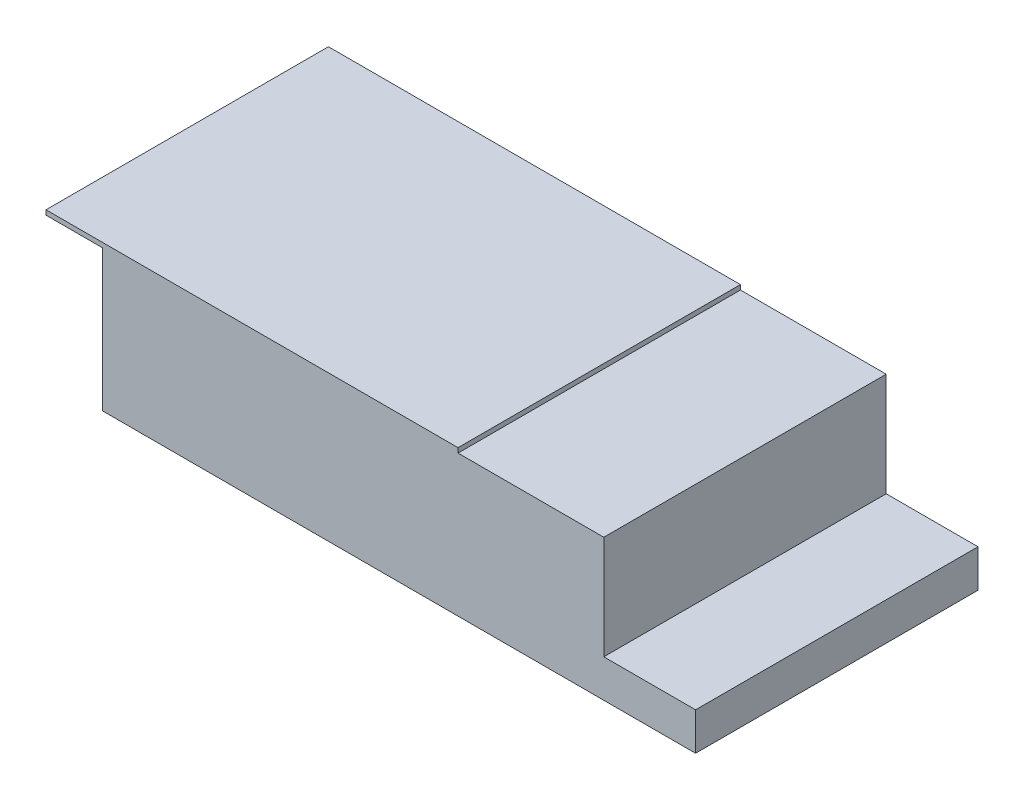
SolidWorks part; units mm, degrees
ref_plane "Front Plane" through (0, 0, 0) normal (0, 0, 1) x (1, 0, 0)
ref_plane "Top Plane" through (0, 0, 0) normal (0, 1, 0) x (1, 0, 0)
ref_plane "Right Plane" through (0, 0, 0) normal (1, 0, 0) x (0, 0, -1)
sketch "Sketch1" plane through (0, 0, 0) normal (0, 1, 0) x (1, 0, 0)
  line L1 (-63, -30) -> (63, -30)
  line L2 (-63, -30) -> (-63, 30)
  line L3 (-63, 30) -> (63, 30)
  line L4 (63, -30) -> (63, 30)
  line L5 (-63, -30) -> (63, 30) construction
  line L6 (-63, 30) -> (63, -30) construction
  point P0 (0, 0)
  dimension "D1" = 126
  dimension "D2" = 60
extrude "Boss-Extrude1" add sketch "Sketch1" along normal blind 30
sketch "Sketch2" plane through (0, 30, 0) normal (0, 1, 0) x (1, 0, 0)
  line L0 (43.5, 30) -> (43.5, -30)
  line L1 (63, 30) -> (-63, 30) construction
  line L2 (-63, -30) -> (63, -30) construction
  line L3 (43.5, -30) -> (63, -30)
  line L4 (63, -30) -> (63, 30)
  line L5 (63, 30) -> (43.5, 30)
  dimension "D1" = 19.5
extrude "Cut-Extrude1" cut sketch "Sketch2" against normal blind 22
sketch "Sketch3" plane through (0, 30, 0) normal (0, 1, 0) x (1, 0, 0)
  line L0 (12.5333, 30) -> (12.5333, -30)
  line L1 (43.5, 30) -> (-63, 30) construction
  line L2 (-63, -30) -> (43.5, -30) construction
  line L3 (12.5333, -30) -> (-75, -30)
  line L4 (-75, -30) -> (-75, 30)
  line L5 (-75, 30) -> (12.5333, 30)
  line L6 (-63, 30) -> (-63, -30) construction
  dimension "D1" = 12
  dimension "D2" = 87.5333
extrude "Boss-Extrude2" add sketch "Sketch3" along normal blind 1
